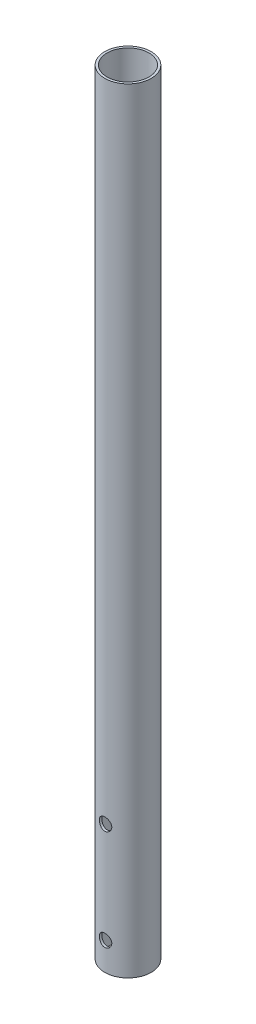
SolidWorks part; units mm, degrees
ref_plane "Front Plane" through (0, 0, 0) normal (0, 0, 1) x (1, 0, 0)
ref_plane "Top Plane" through (0, 0, 0) normal (0, 1, 0) x (1, 0, 0)
ref_plane "Right Plane" through (0, 0, 0) normal (1, 0, 0) x (0, 0, -1)
sketch "Sketch1" plane through (0, 0, 0) normal (0, 1, 0) x (1, 0, 0)
  circle A0 centre (0, 0) radius 13.5
  circle A1 centre (0, 0) radius 15
  dimension "D1" = 30
  dimension "D2" = 27
extrude "Boss-Extrude1" add sketch "Sketch1" along normal blind 500
sketch "Sketch2" plane through (0, 0, 0) normal (0, 0, 1) x (1, 0, 0)
  line L0 (-15, 0) -> (15, 0) construction
  line L1 (15, 0) -> (15, 500) construction
  circle A0 centre (0, 18) radius 4
  circle A1 centre (0, 83) radius 4
  dimension "D1" = 8
  dimension "D2" = 8
  dimension "D3" = 65
  dimension "D4" = 18
  dimension "D5" = 15
  dimension "D6" = 15
extrude "Cut-Extrude1" cut sketch "Sketch2" against normal through all both and the other way through all
